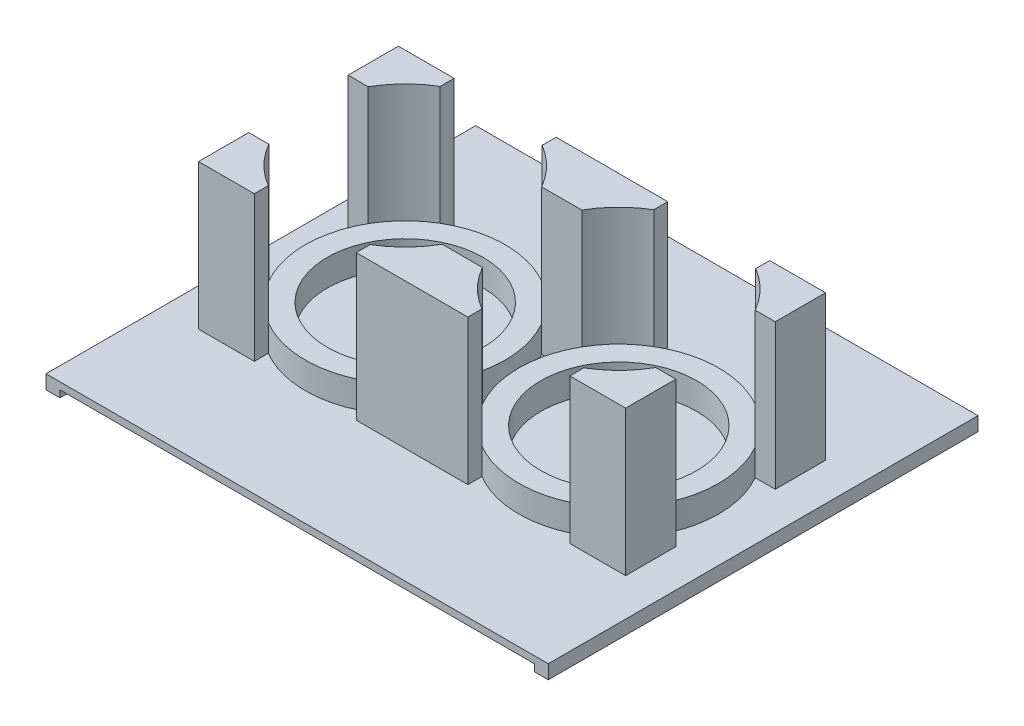
SolidWorks part; units mm, degrees
ref_plane "Front Plane" through (0, 0, 0) normal (0, 0, 1) x (1, 0, 0)
ref_plane "Top Plane" through (0, 0, 0) normal (0, 1, 0) x (1, 0, 0)
ref_plane "Right Plane" through (0, 0, 0) normal (1, 0, 0) x (0, 0, -1)
sketch "Sketch1" plane through (0, 0, 0) normal (0, 1, 0) x (1, 0, 0)
  line L0 (-42.5, 38.5) -> (42.5, 38.5)
  line L1 (0, -38.5) -> (0, 38.5) construction
  line L2 (-42.5, -38.5) -> (42.5, -38.5)
  line L3 (-42.5, 38.5) -> (-42.5, -38.5)
  line L4 (42.5, 38.5) -> (42.5, -38.5)
  point P3 (0, 38.5)
  point P7 (0, 0)
  point P11 (0, -38.5)
  dimension "D1" = 85
  dimension "D3" = 77
extrude "Boss-Extrude1" add sketch "Sketch1" along normal blind 1.25
sketch "Sketch3" plane through (0, 1.25, 0) normal (0, 1, 0) x (1, 0, 0)
  line L0 (-19.1333, 0) -> (19.1333, 0) construction
  line L2 (-1.263, 10.4018) -> (-1.0184, 10.4018)
  line L3 (20.9899, 20.5937) -> (-1.0184, 10.4018)
  line L5 (2.6231, -10.2753) -> (17.2768, -20.5937)
  line L6 (17.2768, -20.5937) -> (36.0397, -11.9047)
  line L7 (36.0397, -11.9047) -> (37.8963, 8.689)
  line L8 (37.8963, 8.689) -> (20.9899, 20.5937)
  line L9 (-19.2063, 20.6771) -> (-37.0767, 10.2753)
  line L10 (-37.0767, 10.2753) -> (-37.0037, -10.4018)
  line L11 (-37.0037, -10.4018) -> (-19.0603, -20.6771)
  line L12 (-19.0603, -20.6771) -> (-1.1899, -10.2753)
  line L13 (-1.1899, -10.2753) -> (-1.263, 10.4018)
  line L14 (-1.263, 10.4018) -> (-19.2063, 20.6771)
  line L15 (-1.1899, -10.2753) -> (2.6231, -10.2753)
  line L16 (2.501, 14.9443) -> (0.5259, -6.9639) [skipped]
  circle A0 centre (19.1333, 0) radius 17.907
  circle A1 centre (-19.1333, 0) radius 17.907
  circle A2 centre (-19.1333, 0) radius 13.97
  circle A3 centre (19.1333, 0) radius 13.97
  circle A4 centre (19.1333, 0) radius 17.907 construction
  circle A5 centre (-19.1333, 0) radius 17.907 construction
  point P4 (0, 0)
  dimension "D1" = 35.814
  dimension "D3" = 27.94
extrude "Boss-Extrude3" add sketch "Sketch3" along normal blind 4.7625
sketch "Sketch4" plane through (0, 1.25, 0) normal (0, 1, 0) x (1, 0, 0)
  line L0 (-19.1333, 17.907) -> (19.1333, 17.907) construction
  line L1 (0, 17.907) -> (-10, 17.907)
  line L2 (-10, 17.907) -> (-10, 15.4027)
  line L3 (0, 17.907) -> (10, 17.907)
  line L4 (10, 17.907) -> (10, 15.4027)
  line L5 (-1.2263, 0) -> (16.6975, 0) construction
  line L6 (-3.5987, 8.907) -> (3.5987, 8.907)
  line L7 (-3.5987, -8.907) -> (3.5987, -8.907)
  line L8 (10, -17.907) -> (10, -15.4027)
  line L9 (0, -17.907) -> (10, -17.907)
  line L10 (-10, -17.907) -> (-10, -15.4027)
  line L11 (0, -17.907) -> (-10, -17.907)
  line L12 (0, 17.907) -> (0, 8.907)
  line L13 (0, -8.907) -> (0, -17.907)
  line L14 (-19.1333, 17.907) -> (-19.1333, 0) construction
  line L15 (19.1333, 17.907) -> (19.1333, 0) construction
  line L16 (-38.2667, -8.907) -> (-38.2667, -17.907)
  line L17 (-38.2667, -17.907) -> (-28.2667, -17.907)
  line L18 (-28.2667, -17.907) -> (-28.2667, -15.4027)
  line L19 (-38.2667, 17.907) -> (-38.2667, 8.907)
  line L20 (-38.2667, 17.907) -> (-28.2667, 17.907)
  line L21 (-28.2667, 17.907) -> (-28.2667, 15.4027)
  line L22 (-38.2667, 8.907) -> (-34.668, 8.907)
  line L23 (-38.2667, -8.907) -> (-34.668, -8.907)
  line L24 (28.2667, -17.907) -> (28.2667, -15.4027)
  line L25 (38.2667, -17.907) -> (28.2667, -17.907)
  line L26 (38.2667, -8.907) -> (38.2667, -17.907)
  line L27 (38.2667, 8.907) -> (34.668, 8.907)
  line L28 (28.2667, 17.907) -> (28.2667, 15.4027)
  line L29 (38.2667, 17.907) -> (28.2667, 17.907)
  line L30 (38.2667, 17.907) -> (38.2667, 8.907)
  line L31 (38.2667, -8.907) -> (34.668, -8.907)
  circle A0 centre (-19.1333, 0) radius 17.907 construction
  circle A1 centre (19.1333, 0) radius 17.907 construction
  arc A2 (10, 15.4027) -> (3.5987, 8.907) centre (19.1333, 0) ccw
  circle A3 centre (-19.1333, 0) radius 17.907 construction
  circle A4 centre (19.1333, 0) radius 17.907 construction
  arc A5 (-3.5987, 8.907) -> (-10, 15.4027) centre (-19.1333, 0) ccw
  arc A6 (-3.5987, -8.907) -> (-10, -15.4027) centre (-19.1333, 0) cw
  arc A7 (10, -15.4027) -> (3.5987, -8.907) centre (19.1333, 0) cw
  arc A8 (-34.668, -8.907) -> (-28.2667, -15.4027) centre (-19.1333, 0) ccw
  arc A9 (-34.668, 8.907) -> (-28.2667, 15.4027) centre (-19.1333, 0) cw
  arc A10 (34.668, -8.907) -> (28.2667, -15.4027) centre (19.1333, 0) cw
  arc A11 (34.668, 8.907) -> (28.2667, 15.4027) centre (19.1333, 0) ccw
  point P0 (0, 8.907)
  point P4 (0, 0)
  point P29 (0, -8.907)
  circle M6 centre (19.1333, 0) radius 17.907
  circle M7 centre (-19.1333, 0) radius 17.907
  dimension "D3" = 9
  dimension "D2" = 10
extrude "Boss-Extrude7" add sketch "Sketch4" along normal blind 26 contours L19 L22 L21 L20 M7 | L23 L16 L17 L18 M7 | L13 L7 L10 L11 M7 | L7 L13 L9 L8 M6 | L12 L1 L2 L6 M7 | L3 L12 L6 L4 M6 | L30 L29 L28 L27 M6 | L26 L31 L24 L25 M6
sketch "Sketch6" plane through (-42.5, 0, 0) normal (-1, 0, 0) x (0, 0, 1)
  line L0 (-38.5, 1.25) -> (-38.5, -1.25)
  line L1 (38.5, 1.25) -> (38.5, -1.25)
  line L2 (-38.5, 1.25) -> (38.5, 1.25) construction
  line L3 (-38.5, 1.25) -> (38.5, 1.25)
  line L4 (-38.5, -1.25) -> (38.5, -1.25)
  dimension "D1" = 2.5
extrude "Boss-Extrude8" add sketch "Sketch6" along normal blind 2.5
mirror "Mirror1" about plane through (0, 0, 0) normal (1, 0, 0) of "Boss-Extrude8"
